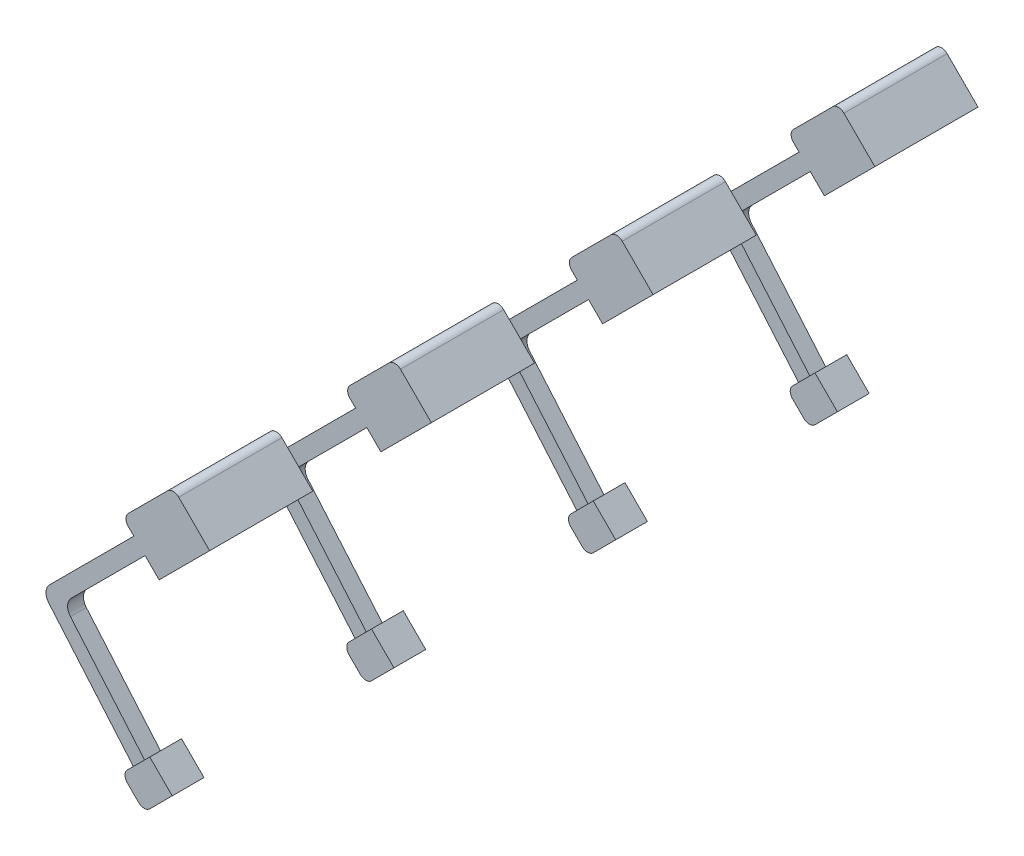
SolidWorks part; units mm, degrees
ref_plane "Front Plane" through (0, 0, 0) normal (0, 0, 1) x (1, 0, 0)
ref_plane "Top Plane" through (0, 0, 0) normal (0, 1, 0) x (1, 0, 0)
ref_plane "Right Plane" through (0, 0, 0) normal (1, 0, 0) x (0, 0, -1)
other "Configuration Table"
sketch "Sketch1" plane through (0, 0, 0) normal (0, 0, 1) x (1, 0, 0)
  line L0 (-261.5942, 287.05) -> (-287.05, 261.5942)
  line L1 (-287.05, 261.5942) -> (-302.6063, 277.1505)
  line L2 (-302.6063, 282.8074) -> (-282.8074, 302.6063)
  line L3 (-277.1505, 302.6063) -> (-261.5942, 287.05)
  arc A0 (-302.6063, 277.1505) -> (-302.6063, 282.8074) centre (-299.7779, 279.9789) cw
  arc A1 (-282.8074, 302.6063) -> (-277.1505, 302.6063) centre (-279.9789, 299.7779) cw
extrude "Coil 2" add sketch "Sketch1" along normal blind 52 from offset 27.9
sketch "Sketch2" plane through (0, 0, 0) normal (0, 0, 1) x (1, 0, 0)
  line L0 (-288.4642, 274.3221) -> (-331.4337, 231.3526)
  line L1 (-331.7585, 223.2191) -> (-288.9548, 172.9712)
  line L2 (-288.9548, 172.9712) -> (-295.0447, 167.7835)
  line L3 (-295.0447, 167.7835) -> (-342.6378, 223.6536)
  line L4 (-342.3129, 231.7871) -> (-294.1211, 279.9789)
  line L5 (-294.1211, 279.9789) -> (-288.4642, 274.3221)
  arc A0 (-331.4337, 231.3526) -> (-331.7585, 223.2191) centre (-327.1911, 227.1099) ccw
  arc A1 (-342.6378, 223.6536) -> (-342.3129, 231.7871) centre (-338.0703, 227.5444) cw
extrude "Plug Lead 2" add sketch "Sketch2" along normal blind 8 from offset 16.1
sketch "Sketch3" plane through (0, 0, 0) normal (0, 0, 1) x (1, 0, 0)
  line L0 (-276.4434, 174.62) -> (-287.7571, 163.3063)
  line L1 (-293.414, 163.3063) -> (-299.0708, 168.9632)
  line L2 (-299.0708, 174.62) -> (-287.7571, 185.9337)
  line L3 (-287.7571, 185.9337) -> (-276.4434, 174.62)
  arc A0 (-287.7571, 163.3063) -> (-293.414, 163.3063) centre (-290.5855, 166.1347) cw
  arc A1 (-299.0708, 168.9632) -> (-299.0708, 174.62) centre (-296.2424, 171.7916) cw
extrude "Plug Boot 2" add sketch "Sketch3" along normal blind 16 from offset 12.1
sketch "Sketch4" plane through (0, 0, 0) normal (0, 0, 1) x (1, 0, 0)
  line L0 (-261.5942, 287.05) -> (-287.05, 261.5942)
  line L1 (-287.05, 261.5942) -> (-302.6063, 277.1505)
  line L2 (-302.6063, 282.8074) -> (-282.8074, 302.6063)
  line L3 (-277.1505, 302.6063) -> (-261.5942, 287.05)
  arc A0 (-302.6063, 277.1505) -> (-302.6063, 282.8074) centre (-299.7779, 279.9789) cw
  arc A1 (-282.8074, 302.6063) -> (-277.1505, 302.6063) centre (-279.9789, 299.7779) cw
extrude "Coil 4" add sketch "Sketch4" along normal blind 52 from offset 139.66
sketch "Sketch5" plane through (0, 0, 0) normal (0, 0, 1) x (1, 0, 0)
  line L0 (-288.4642, 274.3221) -> (-331.4337, 231.3526)
  line L1 (-331.7585, 223.2191) -> (-288.9548, 172.9712)
  line L2 (-288.9548, 172.9712) -> (-295.0447, 167.7835)
  line L3 (-295.0447, 167.7835) -> (-342.6378, 223.6536)
  line L4 (-342.3129, 231.7871) -> (-294.1211, 279.9789)
  line L5 (-294.1211, 279.9789) -> (-288.4642, 274.3221)
  arc A0 (-331.4337, 231.3526) -> (-331.7585, 223.2191) centre (-327.1911, 227.1099) ccw
  arc A1 (-342.6378, 223.6536) -> (-342.3129, 231.7871) centre (-338.0703, 227.5444) cw
extrude "Plug Lead 4" add sketch "Sketch5" along normal blind 8 from offset 95.66
sketch "Sketch6" plane through (0, 0, 0) normal (0, 0, 1) x (1, 0, 0)
  line L0 (-276.4434, 174.62) -> (-287.7571, 163.3063)
  line L1 (-293.414, 163.3063) -> (-299.0708, 168.9632)
  line L2 (-299.0708, 174.62) -> (-287.7571, 185.9337)
  line L3 (-287.7571, 185.9337) -> (-276.4434, 174.62)
  arc A0 (-287.7571, 163.3063) -> (-293.414, 163.3063) centre (-290.5855, 166.1347) cw
  arc A1 (-299.0708, 168.9632) -> (-299.0708, 174.62) centre (-296.2424, 171.7916) cw
extrude "Plug Boot 4" add sketch "Sketch6" along normal blind 16 from offset 99.66
sketch "Sketch7" plane through (0, 0, 0) normal (0, 0, 1) x (1, 0, 0)
  line L0 (-261.5942, 287.05) -> (-287.05, 261.5942)
  line L1 (-287.05, 261.5942) -> (-302.6063, 277.1505)
  line L2 (-302.6063, 282.8074) -> (-282.8074, 302.6063)
  line L3 (-277.1505, 302.6063) -> (-261.5942, 287.05)
  arc A0 (-302.6063, 277.1505) -> (-302.6063, 282.8074) centre (-299.7779, 279.9789) cw
  arc A1 (-282.8074, 302.6063) -> (-277.1505, 302.6063) centre (-279.9789, 299.7779) cw
extrude "Coil 6" add sketch "Sketch7" along normal blind 52 from offset 251.42
sketch "Sketch8" plane through (0, 0, 0) normal (0, 0, 1) x (1, 0, 0)
  line L0 (-288.4642, 274.3221) -> (-331.4337, 231.3526)
  line L1 (-331.7585, 223.2191) -> (-288.9548, 172.9712)
  line L2 (-288.9548, 172.9712) -> (-295.0447, 167.7835)
  line L3 (-295.0447, 167.7835) -> (-342.6378, 223.6536)
  line L4 (-342.3129, 231.7871) -> (-294.1211, 279.9789)
  line L5 (-294.1211, 279.9789) -> (-288.4642, 274.3221)
  arc A0 (-331.4337, 231.3526) -> (-331.7585, 223.2191) centre (-327.1911, 227.1099) ccw
  arc A1 (-342.6378, 223.6536) -> (-342.3129, 231.7871) centre (-338.0703, 227.5444) cw
extrude "Plug Lead 6" add sketch "Sketch8" along normal blind 8 from offset 207.42
sketch "Sketch9" plane through (0, 0, 0) normal (0, 0, 1) x (1, 0, 0)
  line L0 (-276.4434, 174.62) -> (-287.7571, 163.3063)
  line L1 (-293.414, 163.3063) -> (-299.0708, 168.9632)
  line L2 (-299.0708, 174.62) -> (-287.7571, 185.9337)
  line L3 (-287.7571, 185.9337) -> (-276.4434, 174.62)
  arc A0 (-287.7571, 163.3063) -> (-293.414, 163.3063) centre (-290.5855, 166.1347) cw
  arc A1 (-299.0708, 168.9632) -> (-299.0708, 174.62) centre (-296.2424, 171.7916) cw
extrude "Plug Boot 6" add sketch "Sketch9" along normal blind 16 from offset 211.42
sketch "Sketch10" plane through (0, 0, 0) normal (0, 0, 1) x (1, 0, 0)
  line L0 (-261.5942, 287.05) -> (-287.05, 261.5942)
  line L1 (-287.05, 261.5942) -> (-302.6063, 277.1505)
  line L2 (-302.6063, 282.8074) -> (-282.8074, 302.6063)
  line L3 (-277.1505, 302.6063) -> (-261.5942, 287.05)
  arc A0 (-302.6063, 277.1505) -> (-302.6063, 282.8074) centre (-299.7779, 279.9789) cw
  arc A1 (-282.8074, 302.6063) -> (-277.1505, 302.6063) centre (-279.9789, 299.7779) cw
extrude "Coil 8" add sketch "Sketch10" along normal blind 52 from offset 363.18
sketch "Sketch11" plane through (0, 0, 0) normal (0, 0, 1) x (1, 0, 0)
  line L0 (-288.4642, 274.3221) -> (-331.4337, 231.3526)
  line L1 (-331.7585, 223.2191) -> (-288.9548, 172.9712)
  line L2 (-288.9548, 172.9712) -> (-295.0447, 167.7835)
  line L3 (-295.0447, 167.7835) -> (-342.6378, 223.6536)
  line L4 (-342.3129, 231.7871) -> (-294.1211, 279.9789)
  line L5 (-294.1211, 279.9789) -> (-288.4642, 274.3221)
  arc A0 (-331.4337, 231.3526) -> (-331.7585, 223.2191) centre (-327.1911, 227.1099) ccw
  arc A1 (-342.6378, 223.6536) -> (-342.3129, 231.7871) centre (-338.0703, 227.5444) cw
extrude "Plug Lead 8" add sketch "Sketch11" along normal blind 8 from offset 319.18
sketch "Sketch12" plane through (0, 0, 0) normal (0, 0, 1) x (1, 0, 0)
  line L0 (-276.4434, 174.62) -> (-287.7571, 163.3063)
  line L1 (-293.414, 163.3063) -> (-299.0708, 168.9632)
  line L2 (-299.0708, 174.62) -> (-287.7571, 185.9337)
  line L3 (-287.7571, 185.9337) -> (-276.4434, 174.62)
  arc A0 (-287.7571, 163.3063) -> (-293.414, 163.3063) centre (-290.5855, 166.1347) cw
  arc A1 (-299.0708, 168.9632) -> (-299.0708, 174.62) centre (-296.2424, 171.7916) cw
extrude "Plug Boot 8" add sketch "Sketch12" along normal blind 16 from offset 323.18
